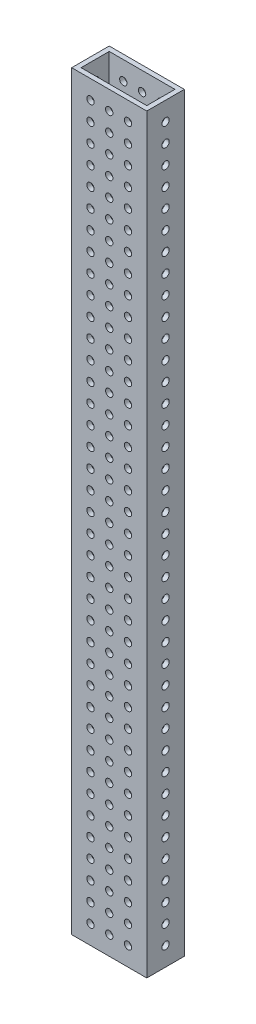
SolidWorks part; units mm, degrees
ref_plane "Front Plane" through (0, 0, 0) normal (0, 0, 1) x (1, 0, 0)
ref_plane "Top Plane" through (0, 0, 0) normal (0, 1, 0) x (1, 0, 0)
ref_plane "Right Plane" through (0, 0, 0) normal (1, 0, 0) x (0, 0, -1)
sketch "Sketch1" plane through (0, 0, 0) normal (0, 1, 0) x (1, 0, 0)
  line L0 (3.175, 22.225) -> (47.625, 22.225)
  line L1 (0, 0) -> (50.8, 0)
  line L2 (0, 0) -> (0, 25.4)
  line L3 (0, 25.4) -> (50.8, 25.4)
  line L4 (50.8, 0) -> (50.8, 25.4)
  line L5 (47.625, 3.175) -> (47.625, 22.225)
  line L6 (3.175, 3.175) -> (47.625, 3.175)
  line L7 (3.175, 3.175) -> (3.175, 22.225)
  dimension "D1" = 50.8
  dimension "D2" = 25.4
  dimension "D3" = 3.175
extrude "Boss-Extrude1" add sketch "Sketch1" along normal mid plane 508
sketch "Sketch2" plane through (0, 0, 0) normal (0, 0, 1) x (1, 0, 0)
  line L0 (0, 254) -> (0, -254) construction
  line L1 (0, 254) -> (50.8, 254) construction
  circle A0 centre (12.7, 241.3) radius 2.4892
  dimension "D1" = 4.9784
  dimension "D2" = 12.7
  dimension "D3" = 12.7
extrude "Cut-Extrude1" cut sketch "Sketch2" against normal through all
pattern_linear "LPattern1" count 39 spacing 12.7 along (0, -1, 0) count 3 spacing 12.7 along (1, 0, 0) of "Cut-Extrude1"
sketch "Sketch3" plane through (50.8, 0, 0) normal (1, 0, 0) x (0, 0, -1)
  line L0 (0, 254) -> (0, -254) construction
  line L1 (0, 254) -> (25.4, 254) construction
  circle A0 centre (12.7, 241.3) radius 2.4892
  dimension "D1" = 4.9784
  dimension "D2" = 12.7
  dimension "D3" = 12.7
extrude "Cut-Extrude2" cut sketch "Sketch3" against normal through all
pattern_linear "LPattern2" count 39 spacing 12.7 along (0, -1, 0) of "Cut-Extrude2"
